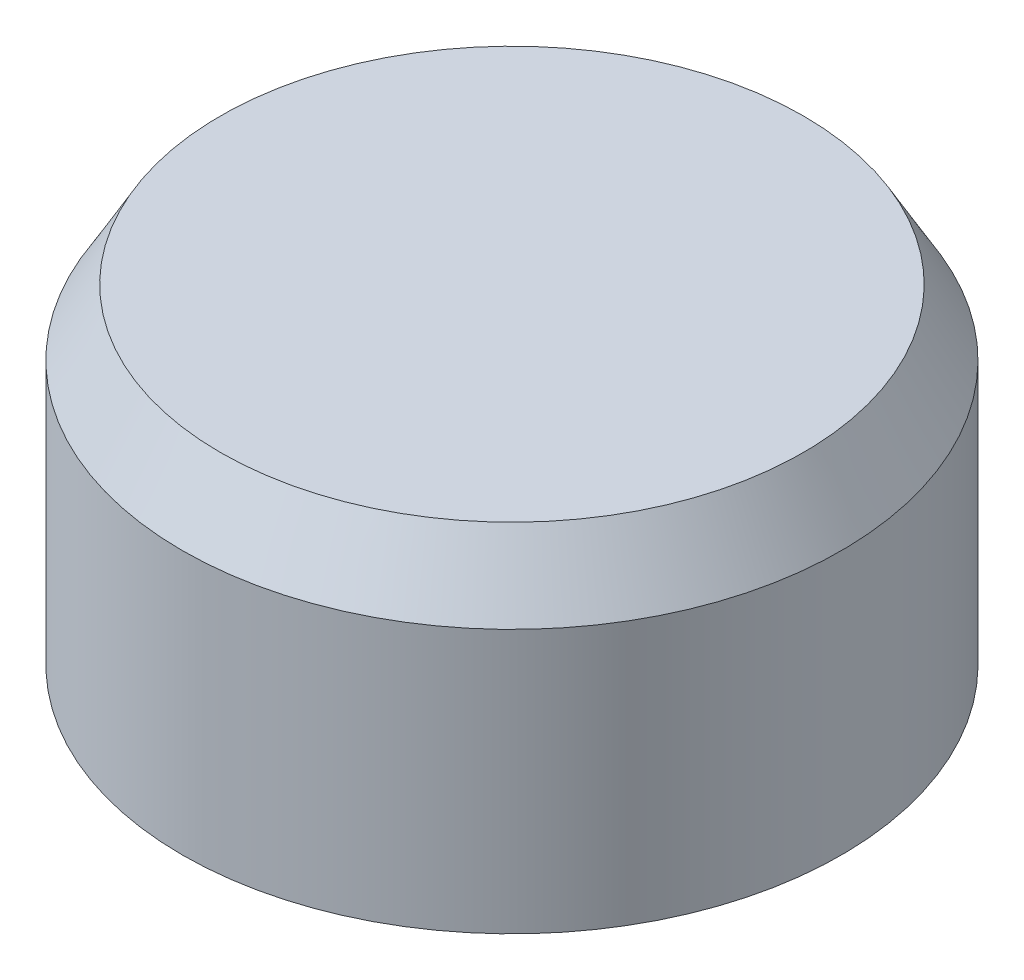
SolidWorks part; units mm, degrees
material "Калифорния"
ref_plane "Спереди" through (0, 0, 0) normal (0, 0, 1) x (1, 0, 0)
ref_plane "Сверху" through (0, 0, 0) normal (0, 1, 0) x (1, 0, 0)
ref_plane "Справа" through (0, 0, 0) normal (1, 0, 0) x (0, 0, -1)
sketch "Контур ручки" plane through (0, 0, 0) normal (0, 1, 0) x (1, 0, 0)
  circle A0 centre (0, 0) radius 10
  dimension "D1" = 20
extrude "Ручка" add sketch "Контур ручки" along normal blind 10
sketch "Эскиз крепежа" plane through (0, 0, 0) normal (0, 1, 0) x (1, 0, 0)
  line L0 (-2, -1.5) -> (2, -1.5)
  arc A0 (2, -1.5) -> (-2, -1.5) centre (0, 0) ccw
  dimension "D1" = 5
  dimension "D2" = 1.5
extrude "Крепёж" cut sketch "Эскиз крепежа" along normal blind 5
chamfer "Фаска1" distance 2 angle 30 1 edges at (0, 10, 10)
